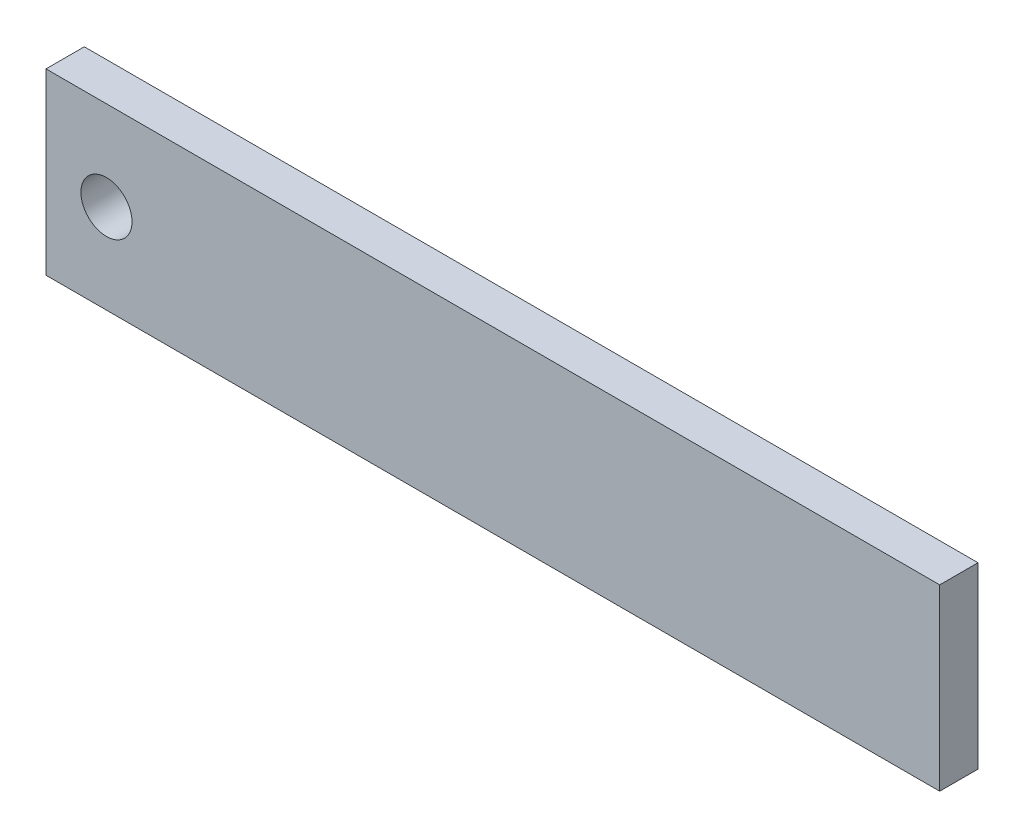
SolidWorks part; units mm, degrees
ref_plane "Alzado" through (0, 0, 0) normal (0, 0, 1) x (1, 0, 0)
ref_plane "Planta" through (0, 0, 0) normal (0, 1, 0) x (1, 0, 0)
ref_plane "Vista lateral" through (0, 0, 0) normal (1, 0, 0) x (0, 0, -1)
sketch "Croquis1" plane through (0, 0, 0) normal (0, 0, 1) x (1, 0, 0)
  line L1 (0, 0) -> (350, 0)
  line L2 (0, 0) -> (0, 70)
  line L3 (0, 70) -> (350, 70)
  line L4 (350, 0) -> (350, 70)
  dimension "D1" = 350
  dimension "D2" = 70
extrude "Saliente-Extruir1" add sketch "Croquis1" along normal blind 15
sketch "Croquis2" plane through (0, 0, 15) normal (0, 0, 1) x (1, 0, 0)
  line L0 (0, 0) -> (350, 0) construction
  circle A0 centre (23.6768, 35) radius 10
  dimension "D1" = 20
  dimension "D2" = 35
extrude "Cortar-Extruir1" cut sketch "Croquis2" against normal blind 130
